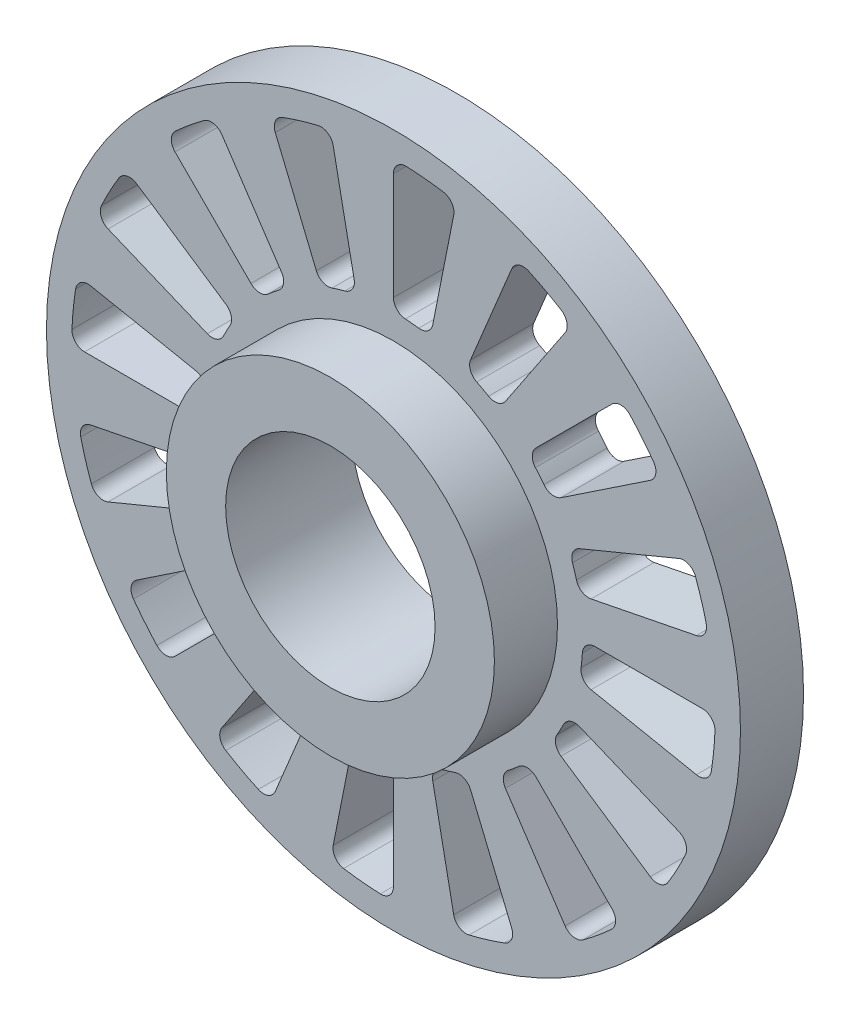
SolidWorks part; units mm, degrees
ref_plane "Front Plane" through (0, 0, 0) normal (0, 0, 1) x (1, 0, 0)
ref_plane "Top Plane" through (0, 0, 0) normal (0, 1, 0) x (1, 0, 0)
ref_plane "Right Plane" through (0, 0, 0) normal (1, 0, 0) x (0, 0, -1)
sketch "Sketch1" plane through (0, 0, 0) normal (0, 0, 1) x (1, 0, 0)
  circle A0 centre (0, 0) radius 4.15
  circle A1 centre (0, 0) radius 13.75
  dimension "D1" = 27.5
  dimension "D2" = 8.3
extrude "Boss-Extrude1" add sketch "Sketch1" along normal blind 2.5
sketch "Sketch2" plane through (0, 0, 2.5) normal (0, 0, 1) x (1, 0, 0)
  circle A0 centre (0, 0) radius 4.15
  circle A1 centre (0, 0) radius 6.5
  circle A2 centre (0, 0) radius 4.15 construction
  circle A3 centre (0, 0) radius 4 construction
  dimension "D1" = 8
  dimension "D2" = 2.5
extrude "Boss-Extrude2" add sketch "Sketch2" along normal blind 2.5
sketch "Sketch5" plane through (0, 0, 0) normal (0, 0, 1) x (1, 0, 0)
  line L0 (0, 0) -> (0, 7.5) construction
  line L1 (0, 7.5) -> (0, 12.75)
  line L2 (0, 0) -> (1.4632, 7.3559) construction
  line L3 (1.4632, 7.3559) -> (2.4874, 12.505)
  circle A0 centre (0, 0) radius 12.75
  circle A1 centre (0, 0) radius 7.5
  circle A2 centre (0, 0) radius 13.75 construction
  circle A3 centre (0, 0) radius 6.5 construction
  dimension "D1" = 1
  dimension "D2" = 1
  dimension "D3" = 11.25
extrude "Cut-Extrude1" cut sketch "Sketch5" along normal through all contours A1 L3 A0 L1
fillet "Fillet1" radius 0.5 4 edges at (1.4632, 7.3559, 1.25) (2.4874, 12.505, 1.25) (0, 7.5, 1.25) (0, 12.75, 1.25)
pattern_circular "CirPattern1" count 16 over 360 about axis through (0, 0, 0) along (0, 0, 1) of "Cut-Extrude1", "Fillet1"
